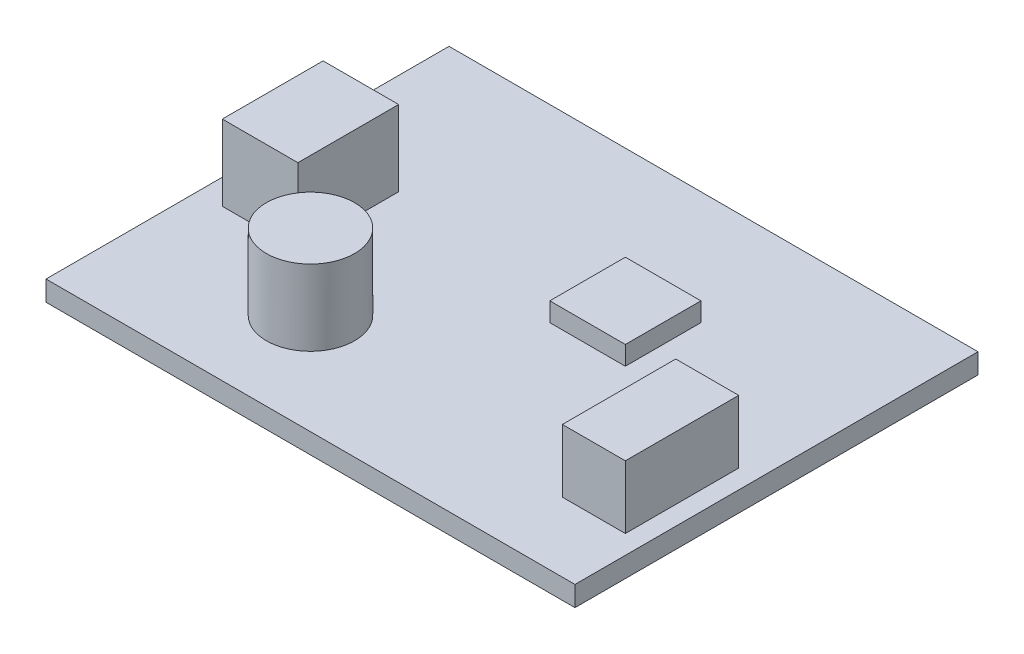
SolidWorks part; units mm, degrees
ref_plane "Front Plane" through (0, 0, 0) normal (0, 0, 1) x (1, 0, 0)
ref_plane "Top Plane" through (0, 0, 0) normal (0, 1, 0) x (1, 0, 0)
ref_plane "Right Plane" through (0, 0, 0) normal (1, 0, 0) x (0, 0, -1)
other "Configuration Table"
sketch "Sketch1" plane through (0, 0, 0) normal (0, 1, 0) x (1, 0, 0)
  line L1 (-21, -16) -> (21, -16)
  line L2 (-21, -16) -> (-21, 16)
  line L3 (-21, 16) -> (21, 16)
  line L4 (21, -16) -> (21, 16)
  line L5 (-21, -16) -> (21, 16) construction
  line L6 (-21, 16) -> (21, -16) construction
extrude "PCB" add sketch "Sketch1" along normal blind 1.6
sketch "Sketch2" plane through (0, 0, 0) normal (0, 1, 0) x (1, 0, 0)
  line L1 (2, 1) -> (8, 1)
  line L2 (2, 1) -> (2, 7)
  line L3 (2, 7) -> (8, 7)
  line L4 (8, 1) -> (8, 7)
  line L5 (2, 1) -> (8, 7) construction
  line L6 (2, 7) -> (8, 1) construction
extrude "IC" add sketch "Sketch2" along normal blind 1.5 from offset 1.6
sketch "Sketch3" plane through (0, 0, 0) normal (0, 1, 0) x (1, 0, 0)
  line L1 (14.5, -10.5) -> (19.5, -10.5)
  line L2 (14.5, -10.5) -> (14.5, -1.5)
  line L3 (14.5, -1.5) -> (19.5, -1.5)
  line L4 (19.5, -10.5) -> (19.5, -1.5)
  line L5 (14.5, -10.5) -> (19.5, -1.5) construction
  line L6 (14.5, -1.5) -> (19.5, -10.5) construction
extrude "Out_Connector" add sketch "Sketch3" along normal blind 5 from offset 1.6
sketch "Sketch4" plane through (0, 0, 0) normal (0, 1, 0) x (1, 0, 0)
  line L1 (-19, -4) -> (-13, -4)
  line L2 (-19, -4) -> (-19, 4)
  line L3 (-19, 4) -> (-13, 4)
  line L4 (-13, -4) -> (-13, 4)
  line L5 (-19, -4) -> (-13, 4) construction
  line L6 (-19, 4) -> (-13, -4) construction
extrude "Probe_Connector" add sketch "Sketch4" along normal blind 6 from offset 1.6
sketch "Sketch5" plane through (0, 0, 0) normal (0, 1, 0) x (1, 0, 0)
  circle A0 centre (-8, -8) radius 3.5
extrude "Trim_Pot" add sketch "Sketch5" along normal blind 6 from offset 1.6
equation "\"sig_L\"= 42.0   'ASSUMPTION: TDS / ORP signal board L (NOT in PDF table - designer guess)"
equation "\"sig_W\"= 32.0   'ASSUMPTION: TDS / ORP signal board W (NOT in PDF table - designer guess)"
equation "\"pcb_t\"= 1.6   'ASSUMPTION: PCB thickness (standard)"
equation "\"D1@PCB\" = \"pcb_t\""
